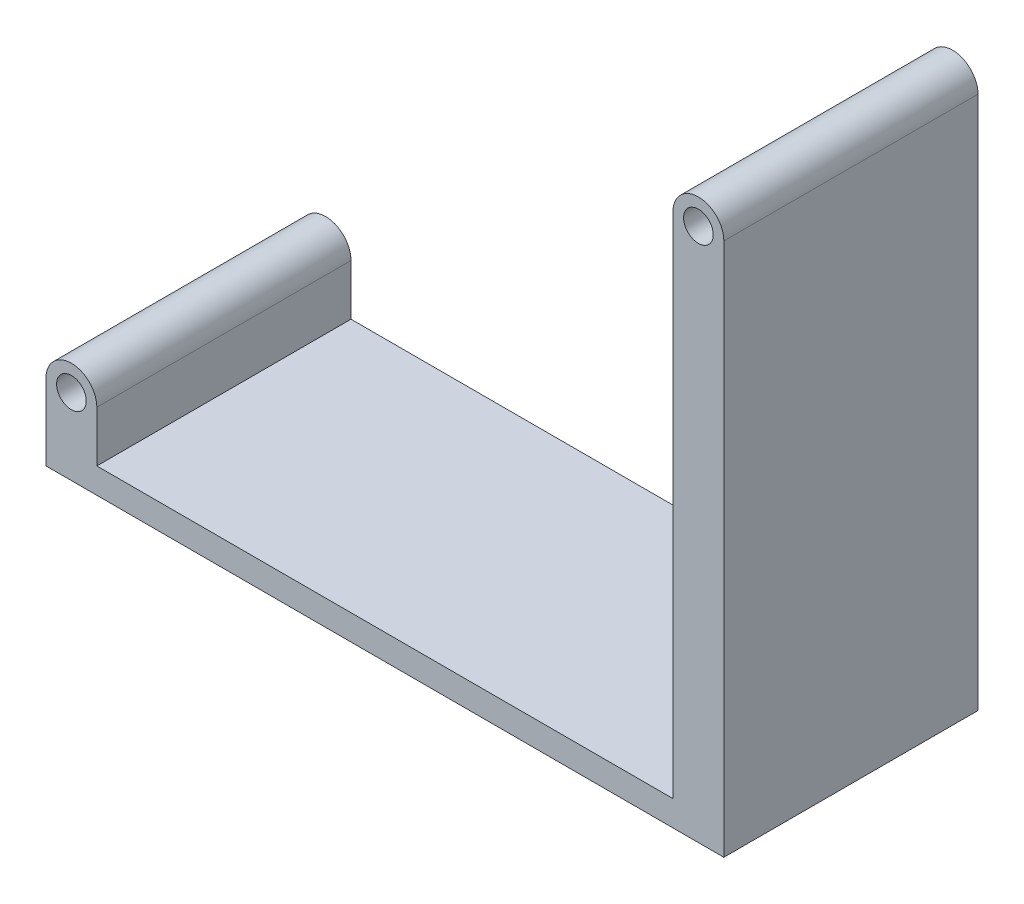
SolidWorks part; units mm, degrees
ref_plane "Front Plane" through (0, 0, 0) normal (0, 0, 1) x (1, 0, 0)
ref_plane "Top Plane" through (0, 0, 0) normal (0, 1, 0) x (1, 0, 0)
ref_plane "Right Plane" through (0, 0, 0) normal (1, 0, 0) x (0, 0, -1)
sketch "Sketch1" plane through (0, 0, 0) normal (0, 0, 1) x (1, 0, 0)
  line L1 (0, 0) -> (80, 0)
  line L2 (0, 0) -> (0, 3)
  line L3 (0, 3) -> (80, 3)
  line L4 (80, 0) -> (80, 3)
  line L5 (0, 3) -> (6, 3)
  line L6 (0, 3) -> (0, 9)
  line L7 (0, 9) -> (6, 9)
  line L8 (6, 3) -> (6, 9)
  line L9 (80, 3) -> (74, 3)
  line L10 (80, 3) -> (80, 63)
  line L11 (80, 63) -> (74, 63)
  line L12 (74, 3) -> (74, 63)
  line L13 (74, 63) -> (80, 63)
  line L14 (74, 63) -> (74, 65.6736)
  line L15 (74, 65.6736) -> (80, 65.6736)
  line L16 (80, 63) -> (80, 65.6736)
  circle A0 centre (3, 9) radius 3
  circle A1 centre (77, 63) radius 3
  circle A2 centre (3, 9) radius 1.75
  circle A3 centre (77, 63) radius 1.75
  dimension "D1" = 3.5
  dimension "D2" = 6
  dimension "D6" = 6
  dimension "D7" = 3.5
  dimension "D3" = 6
  dimension "D4" = 3
  dimension "D5" = 80
  dimension "D8" = 6
  dimension "D9" = 6
  dimension "D10" = 60
extrude "Boss-Extrude1" add sketch "Sketch1" along normal blind 30 contours A1 L12 L3 L10 | A3 L11 A1 L15 | A3 L11 A1 | L15 A1 | A2 L7 A0 | A2 L7 A0 | A0 L6 L3 L8 | L1 L4 L3 L2
